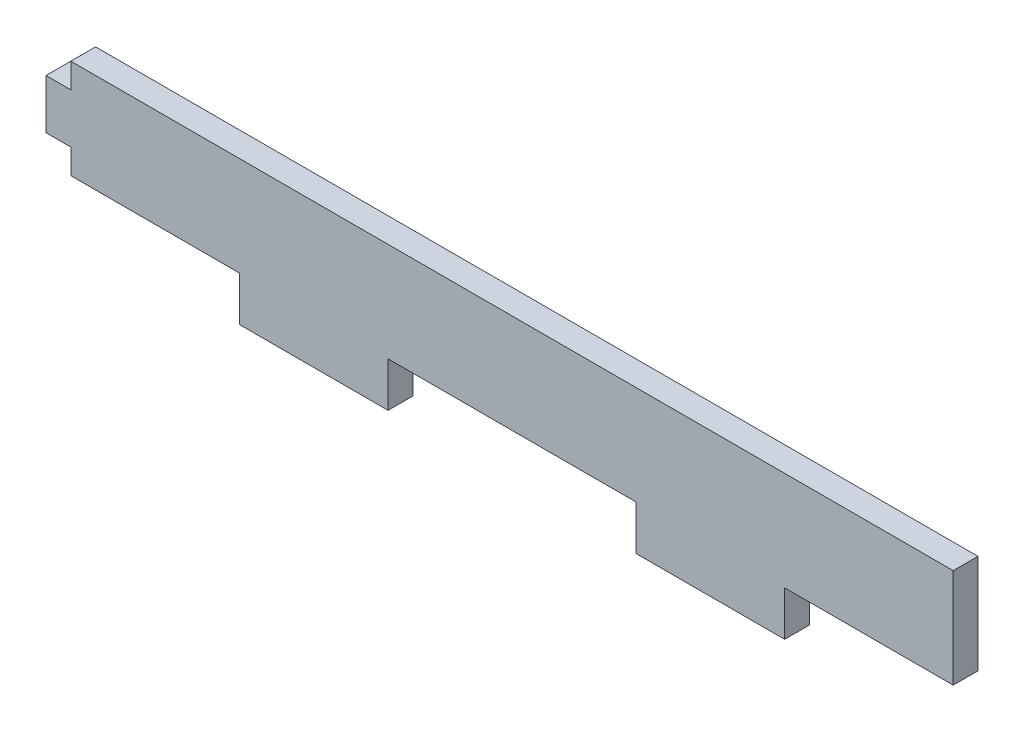
SolidWorks part; units mm, degrees
ref_plane "Front Plane" through (0, 0, 0) normal (0, 0, 1) x (1, 0, 0)
ref_plane "Top Plane" through (0, 0, 0) normal (0, 1, 0) x (1, 0, 0)
ref_plane "Right Plane" through (0, 0, 0) normal (1, 0, 0) x (0, 0, -1)
sketch "Sketch1" plane through (0, 0, 0) normal (0, 0, 1) x (1, 0, 0)
  line L0 (5, 5.5) -> (5, 10.5)
  line L3 (5, 25.5) -> (183, 25.5)
  line L7 (5, 5.5) -> (39, 5.5)
  line L9 (5, 20.5) -> (0, 20.5)
  line L10 (94, 0) -> (94, 40.5716) construction
  line L11 (5, 10.5) -> (0, 10.5)
  line L12 (5, 20.5) -> (5, 25.5)
  line L13 (-0.5, 25.5) -> (188.5, 25.5) construction
  line L14 (-0.5, 0) -> (-0.5, 25.5) construction
  line L15 (0, 10.5) -> (0, 20.5)
  line L16 (5, 5.5) -> (5, 20) construction
  line L17 (39, 5.5) -> (39, -3.5)
  line L19 (69, 5.5) -> (69, -3.5)
  line L21 (119, 5.5) -> (119, -3.5)
  line L23 (149, 5.5) -> (149, -3.5)
  line L25 (188.5, 0) -> (188.5, 25.5) construction
  line L26 (69, 5.5) -> (119, 5.5)
  line L27 (5, 5.5) -> (183, 5.5) construction
  line L28 (149, 5.5) -> (183, 5.5)
  line L29 (-0.5, 0) -> (188.5, 0) construction
  line L30 (39, -3.5) -> (69, -3.5)
  line L31 (119, -3.5) -> (149, -3.5)
  line L32 (183, 5.5) -> (183, 20) construction
  line L33 (5, 20) -> (183, 20) construction
  line L34 (183, 5.5) -> (183, 25.5)
  dimension "D2" = 25
  dimension "D4" = 5
  dimension "D5" = 10
  dimension "D6" = 30
  dimension "D7" = 25
  dimension "D8" = 30
  dimension "D9" = 29
  dimension "D10" = 9
  dimension "D11" = 5
  dimension "D12" = 178
  dimension "D3" = 5.5
extrude "Boss-Extrude1" add sketch "Sketch1" along normal blind 5
